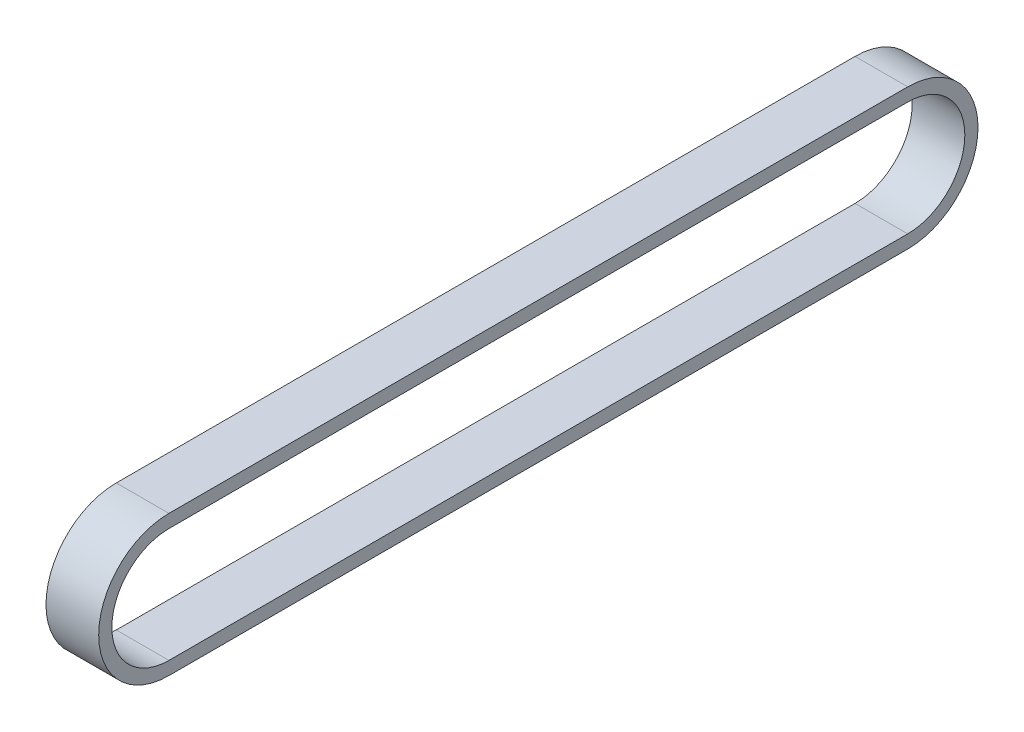
SolidWorks part; units mm, degrees
ref_plane "前视基准面" through (0, 0, 0) normal (0, 0, 1) x (1, 0, 0)
ref_plane "上视基准面" through (0, 0, 0) normal (0, 1, 0) x (1, 0, 0)
ref_plane "右视基准面" through (0, 0, 0) normal (1, 0, 0) x (0, 0, -1)
other "Configuration Table"
sketch "草图1" plane through (0, 0, 0) normal (1, 0, 0) x (0, 0, -1)
  circle A0 centre (0, 0) radius 18.5413
extrude "凸台-拉伸1" add sketch "草图1" along normal blind 10
sketch "草图2" plane through (0, 0, 0) normal (-1, 0, 0) x (0, 0, 1)
  line L4 (-46.0122, -85.5975) -> (445.2378, -85.5975) construction
  line L5 (-46.0122, -5.5975) -> (445.2378, -5.5975)
  line L6 (-46.0122, -165.5975) -> (445.2378, -165.5975)
  circle A0 centre (-46.0122, -85.5975) radius 65
  circle A1 centre (445.2378, -85.5975) radius 65
  arc A4 (-46.0122, -5.5975) -> (-46.0122, -165.5975) centre (-46.0122, -85.5975) ccw
  arc A5 (445.2378, -165.5975) -> (445.2378, -5.5975) centre (445.2378, -85.5975) ccw
  point P15 (199.6128, -85.5975)
extrude "凸台-拉伸2" add sketch "草图2" against normal blind 60
sketch "草图3" plane through (0, 0, 0) normal (-1, 0, 0) x (0, 0, 1)
  line L0 (-32.2719, -5.5975) -> (45.2522, -5.5975)
  line L3 (45.2522, -5.5975) -> (36.7997, 39.5712)
  line L4 (36.7997, 39.5712) -> (-16.4201, 39.5712)
  line L5 (-16.4201, 39.5712) -> (-32.2719, -5.5975)
  line L6 (445.2378, -5.5975) -> (17.6762, -5.5975) construction
extrude "切除-拉伸1" cut sketch "草图3" against normal through all both and the other way through all
sketch "草图4" plane through (0, 0, 0) normal (-1, 0, 0) x (0, 0, 1)
  line L4 (-46.0122, -20.5975) -> (-46.0122, -150.5975)
  line L5 (-46.0122, -150.5975) -> (445.2378, -150.5975)
  line L6 (445.2378, -150.5975) -> (445.2378, -20.5975)
  line L7 (445.2378, -20.5975) -> (-46.0122, -20.5975)
  circle A2 centre (-46.0122, -85.5975) radius 65 construction
  circle A3 centre (445.2378, -85.5975) radius 65 construction
extrude "切除-拉伸2" cut sketch "草图4" against normal through all both and the other way through all
sketch "草图6" plane through (60, 0, 0) normal (1, 0, 0) x (0, 0, -1)
  line L0 (-795.2378, -85.5975) -> (46.0122, -85.5975) construction
  line L1 (-795.2378, -5.5975) -> (46.0122, -5.5975)
  line L2 (-795.2378, -165.5975) -> (46.0122, -165.5975)
  line L3 (-870.8701, -0.5975) -> (129.1299, -0.5975) construction
  line L4 (-795.2378, -20.5975) -> (46.0122, -20.5975)
  line L5 (-795.2378, -150.5975) -> (46.0122, -150.5975)
  arc A0 (-795.2378, -20.5975) -> (-795.2378, -150.5975) centre (-795.2378, -85.5975) ccw
  arc A1 (46.0122, -150.5975) -> (46.0122, -20.5975) centre (46.0122, -85.5975) ccw
  arc A2 (-795.2378, -5.5975) -> (-795.2378, -165.5975) centre (-795.2378, -85.5975) ccw
  arc A3 (46.0122, -165.5975) -> (46.0122, -5.5975) centre (46.0122, -85.5975) ccw
  point P6 (-374.6128, -85.5975)
  dimension "D1" = 5
extrude "凸台-拉伸3" add sketch "草图6" against normal up to surface (60 mm away) up to face at (0, -85.5975, 199.6128)
sketch "草图7" plane through (60, 0, 0) normal (1, 0, 0) x (0, 0, -1)
  line L0 (-547.5662, -20.5975) -> (-408.9425, -20.5975)
  line L1 (-491.8747, -20.5975) -> (-795.2378, -20.5975) construction
  line L2 (-445.2378, -20.5975) -> (46.0122, -20.5975) construction
  line L3 (-408.9425, -20.5975) -> (-408.9425, -150.5975)
  line L4 (46.0122, -150.5975) -> (-445.2378, -150.5975) construction
  line L5 (-408.9425, -150.5975) -> (-543.9219, -150.5975)
  line L6 (-795.2378, -150.5975) -> (-491.8747, -150.5975) construction
  line L7 (-543.9219, -150.5975) -> (-547.5662, -20.5975)
extrude "切除-拉伸3" cut sketch "草图7" against normal blind 229
